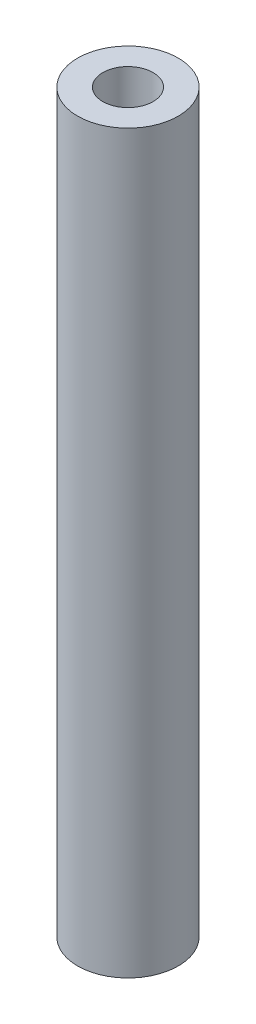
SolidWorks part; units mm, degrees
material "PET"
ref_plane "Front Plane" through (0, 0, 0) normal (0, 0, 1) x (1, 0, 0)
ref_plane "Top Plane" through (0, 0, 0) normal (0, 1, 0) x (1, 0, 0)
ref_plane "Right Plane" through (0, 0, 0) normal (1, 0, 0) x (0, 0, -1)
sketch "Sketch1" plane through (0, 0, 0) normal (0, 1, 0) x (1, 0, 0)
  circle A0 centre (0, 0) radius 4
  circle A1 centre (0, 0) radius 2
  dimension "D1" = 4
  dimension "D2" = 8
extrude "Boss-Extrude1" add sketch "Sketch1" along normal blind 58.5
